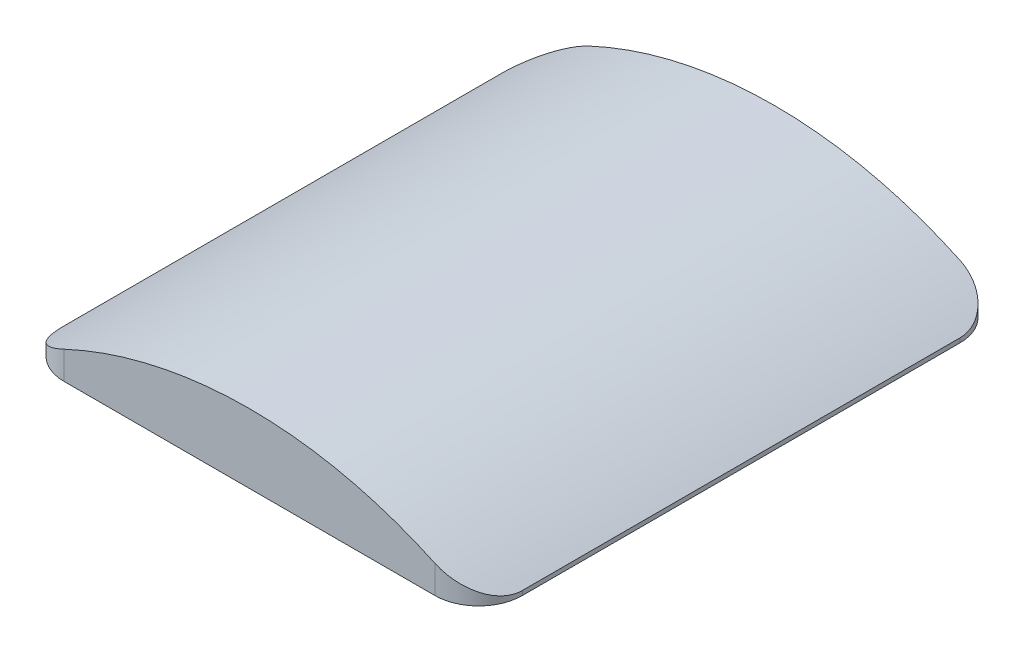
SolidWorks part; units mm, degrees
ref_plane "Front Plane" through (0, 0, 0) normal (0, 0, 1) x (1, 0, 0)
ref_plane "Top Plane" through (0, 0, 0) normal (0, 1, 0) x (1, 0, 0)
ref_plane "Right Plane" through (0, 0, 0) normal (1, 0, 0) x (0, 0, -1)
sketch "Sketch1" plane through (0, 0, 0) normal (0, 0, 1) x (1, 0, 0)
  line L0 (0, 0) -> (0, -11.0551) construction
  line L1 (52.375, -25.8679) -> (52.375, -26.8679)
  line L2 (52.375, -26.8679) -> (-52.375, -26.8679)
  line L3 (-52.375, -26.8679) -> (-52.375, -25.8679)
  arc A0 (-52.375, -25.8679) -> (52.375, -25.8679) centre (0, -111.0551) cw
  point P9 (0, -26.8679)
  dimension "D1" = 100
  dimension "D2" = 104.75
  dimension "D3" = 1
extrude "Boss-Extrude1" add sketch "Sketch1" along normal mid plane 120
fillet "Fillet1" radius 10 4 edges at (-52.375, -26.3679, 60) (-52.375, -26.3679, -60) (52.375, -26.3679, -60) (52.375, -26.3679, 60)
